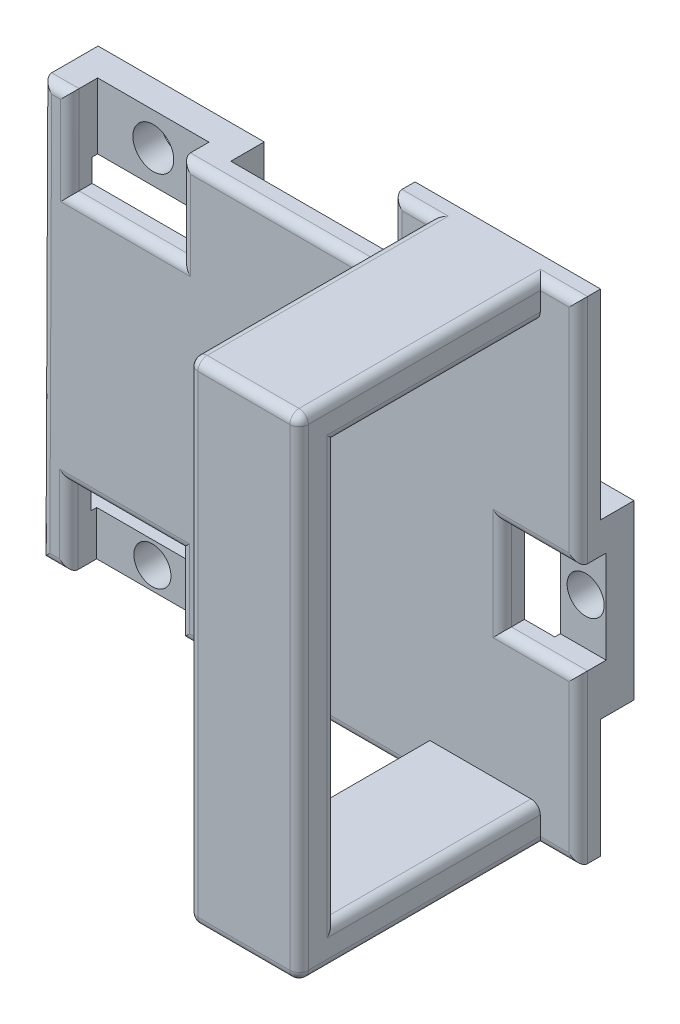
SolidWorks part; units mm, degrees
ref_plane "Płaszczyzna przednia" through (0, 0, 0) normal (0, 0, 1) x (1, 0, 0)
ref_plane "Płaszczyzna górna" through (0, 0, 0) normal (0, 1, 0) x (1, 0, 0)
ref_plane "Płaszczyzna prawa" through (0, 0, 0) normal (1, 0, 0) x (0, 0, -1)
sketch "Szkic1" plane through (0, 0, 158.8329) normal (0, 0, 1) x (1, 0, 0)
  line L0 (-31.9233, -22.4743) -> (2.0767, -22.4743) construction
  line L1 (-19.5, -20.0743) -> (-10.4467, -20.0743)
  line L2 (-19.5, -20.0743) -> (-19.5, -22.4743)
  line L3 (-19.5, -22.4743) -> (-10.4467, -22.4743)
  line L4 (-10.4467, -20.0743) -> (-10.4467, -22.4743)
  line L5 (-19.5, -20.0743) -> (-10.4467, -22.4743) construction
  line L6 (-19.5, -22.4743) -> (-10.4467, -20.0743) construction
  line L12 (9.4816, -6.7768) -> (7.0127, -6.7768)
  line L13 (9.4816, -6.7768) -> (9.4816, -16.0838)
  line L14 (-19.4004, -3.549) -> (-10.4467, -3.549)
  line L15 (-19.4004, -3.549) -> (-19.4004, 0)
  line L16 (-19.4004, 0) -> (-10.4467, 0)
  line L17 (-10.4467, -3.549) -> (-10.4467, 0)
  line L18 (-19.4004, -3.549) -> (-10.4467, 0) construction
  line L19 (-19.4004, 0) -> (-10.4467, -3.549) construction
  line L20 (9.4816, -16.0838) -> (7.0127, -16.0838)
  line L21 (7.0127, -6.7768) -> (7.0127, -16.0838)
  circle A0 centre (8.3767, -10.9743) radius 1 construction
  circle A1 centre (-14.9733, -21.2743) radius 1 construction
  circle A2 centre (-14.9235, -1.7745) radius 1.1 construction
  circle A3 centre (8.3767, -10.9743) radius 1
  circle A4 centre (-14.9733, -21.2743) radius 1
  circle A5 centre (-14.9235, -1.7745) radius 1.1
extrude "Dodanie-wyciągnięcie1" add sketch "Szkic1" along normal blind 1.8
sketch "Szkic2" plane through (0, 0, 160.6329) normal (0, 0, 1) x (1, 0, 0)
  line L0 (9.4816, -16.0838) -> (9.4816, -6.7768) construction
  line L1 (9.4816, 0) -> (-19.4004, 0)
  line L2 (9.4816, 0) -> (9.4816, -22.4743)
  line L3 (9.4816, -22.4743) -> (-19.5, -22.4743)
  line L4 (-19.4004, 0) -> (-19.5, -22.4743)
  circle A0 centre (8.3767, -10.9743) radius 1 construction
  circle A1 centre (-14.9733, -21.2743) radius 1 construction
  circle A2 centre (-14.9235, -1.7745) radius 1.1 construction
  circle A3 centre (8.3767, -10.9743) radius 1
  circle A4 centre (-14.9733, -21.2743) radius 1
  circle A5 centre (-14.9235, -1.7745) radius 1.1
extrude "Dodanie-wyciągnięcie2" add sketch "Szkic2" along normal blind 1.2
sketch "Szkic3" plane through (0, 0, 161.8329) normal (0, 0, 1) x (1, 0, 0)
  line L1 (-19.4893, -20.0743) -> (-19.5, -20.0743) construction
  line L3 (-17.9235, -4.7745) -> (-11.9235, -4.7745)
  line L4 (-19.4893, -20.0743) -> (-19.5, -20.0743)
  line L5 (5.3767, -8.4743) -> (5.3767, -13.4743)
  line L7 (-11.9733, -18.2743) -> (-17.9733, -18.2743)
  line L8 (9.4816, 0) -> (-19.4004, 0) construction
  line L9 (-17.9235, -4.7745) -> (-11.9235, -4.7745)
  line L10 (-17.9235, -4.7745) -> (-17.9235, 0)
  line L11 (-17.9235, 0) -> (-11.9235, 0)
  line L12 (-11.9235, -4.7745) -> (-11.9235, 0)
  line L13 (9.4816, -22.4743) -> (9.4816, 0) construction
  line L14 (5.3767, -8.4743) -> (9.4816, -8.4743)
  line L15 (5.3767, -8.4743) -> (5.3767, -13.4743)
  line L16 (5.3767, -13.4743) -> (9.4816, -13.4743)
  line L17 (9.4816, -8.4743) -> (9.4816, -13.4743)
  line L18 (-19.5, -22.4743) -> (9.4816, -22.4743) construction
  line L19 (-17.9733, -18.2743) -> (-11.9733, -18.2743)
  line L20 (-17.9733, -18.2743) -> (-17.9733, -22.4743)
  line L21 (-17.9733, -22.4743) -> (-11.9733, -22.4743)
  line L22 (-11.9733, -18.2743) -> (-11.9733, -22.4743)
  circle A0 centre (-14.9235, -1.7745) radius 1.1 construction
  circle A1 centre (8.3767, -10.9743) radius 1 construction
  circle A2 centre (-14.9733, -21.2743) radius 1 construction
  circle A3 centre (-14.9235, -1.7745) radius 1.1
  circle A4 centre (8.3767, -10.9743) radius 1
  circle A5 centre (-14.9733, -21.2743) radius 1
  line M11 (9.4816, -22.4743) -> (9.4816, 0)
  line M12 (9.4816, 0) -> (-19.4004, 0)
  line M14 (-19.5, -22.4743) -> (9.4816, -22.4743)
  circle M15 centre (8.3767, -10.9743) radius 1
  circle M16 centre (-14.9733, -21.2743) radius 1
  circle M17 centre (-14.9235, -1.7745) radius 1.1
  dimension "D1" = 3
  dimension "D2" = 3
  dimension "D3" = 2.5
  dimension "D4" = 2.5
  dimension "D5" = 3
  dimension "D6" = 3
  dimension "D7" = 3
  dimension "D8" = 3
  dimension "D9" = 3
extrude "Wytnij-wyciągnięcie1" cut sketch "Szkic3" against normal blind 1.5 contours L5 L16 L14 M11 M15 | L3 L12 L10 M12 M17 | L22 L7 L20 M14 M16
sketch "Szkic7" plane through (0, 0, 0) normal (0, 1, 0) x (1, 0, 0)
  line L0 (9.4816, -160.6329) -> (-10.4467, -160.6329) construction
  line L1 (9.4816, -161.8329) -> (-0.5184, -161.8329)
  line L2 (9.4816, -161.8329) -> (9.4816, -160.6329)
  line L3 (9.4816, -160.6329) -> (-0.5184, -160.6329)
  line L4 (-0.5184, -161.8329) -> (-0.5184, -160.6329)
  dimension "D1" = 10
extrude "Dodanie-wyciągnięcie3" add sketch "Szkic7" along normal blind 4
sketch "Szkic8" plane through (0, 0, 161.8329) normal (0, 0, 1) x (1, 0, 0)
  line L0 (-0.5184, 4) -> (9.4816, 4) construction
  line L1 (7.432, 4) -> (1.4816, 4)
  line L2 (7.432, 4) -> (7.432, 2)
  line L3 (7.432, 2) -> (1.4816, 2)
  line L4 (1.4816, 4) -> (1.4816, 2)
  line L6 (-11.9733, -22.4743) -> (9.4816, -22.4743) construction
  line L7 (7.432, -22.4743) -> (1.4816, -22.4743)
  line L8 (7.432, -22.4743) -> (7.432, -20.4743)
  line L9 (7.432, -20.4743) -> (1.4816, -20.4743)
  line L10 (1.4816, -22.4743) -> (1.4816, -20.4743)
  line L11 (9.4816, -22.4743) -> (9.4816, -13.4743) construction
  line L12 (9.4816, -8.4743) -> (9.4816, 4) construction
  dimension "D1" = 2
  dimension "D2" = 8
  dimension "D3" = 8
extrude "Dodanie-wyciągnięcie4" add sketch "Szkic8" along normal blind 11
sketch "Szkic9" plane through (0, 0, 172.8329) normal (0, 0, 1) x (1, 0, 0)
  line L1 (7.432, 4) -> (1.4816, 4)
  line L2 (7.432, 4) -> (7.432, -22.4743)
  line L3 (7.432, -22.4743) -> (1.4816, -22.4743)
  line L4 (1.4816, 4) -> (1.4816, -22.4743)
extrude "Dodanie-wyciągnięcie5" add sketch "Szkic9" along normal blind 2
fillet "Zaokrąglenie4" radius 0.5 33 edges at (0.4816, 4, 161.8329) (-0.5184, 2, 161.8329) (-6.221, 0, 161.8329) (-11.9235, -2.3872, 161.8329) (-14.9235, -4.7745, 161.8329) (-17.9235, -2.3872, 161.8329) (-18.662, 0, 161.8329) (-19.4502, -11.2371, 161.8329) (-18.7366, -22.4743, 161.8329) (-17.9733, -20.3743, 161.8329) (-14.9733, -18.2743, 161.8329) (-11.9733, -20.3743, 161.8329) (-5.2459, -22.4743, 161.8329) (8.4568, -22.4743, 161.8329) (8.4568, 4, 161.8329) (9.4816, -2.2371, 161.8329) (7.4291, -8.4743, 161.8329) (5.3767, -10.9743, 161.8329) (7.4291, -13.4743, 161.8329) (9.4816, -17.9743, 161.8329) (7.432, 4, 168.3329) (7.432, 2, 167.3329) (7.432, -9.2371, 172.8329) (7.432, -20.4743, 167.3329) (7.432, -9.2371, 174.8329) (4.4568, 4, 174.8329) (1.4816, -9.2371, 174.8329) (1.4816, -9.2371, 172.8329) (1.4816, 4, 168.3329) (1.4816, 2, 167.3329) (1.4816, -22.4743, 168.3329) (4.4568, -22.4743, 174.8329) (7.432, -22.4743, 168.3329)
